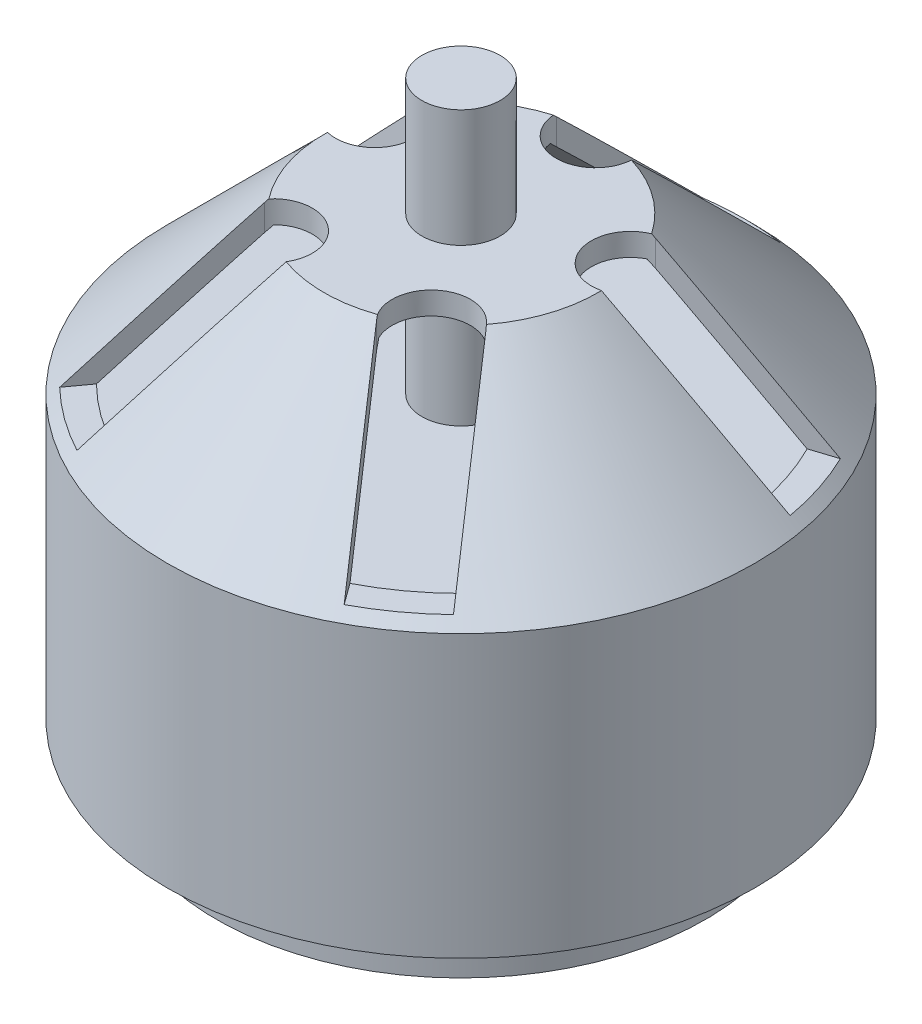
SolidWorks part; units mm, degrees
ref_plane "Front Plane" through (0, 0, 0) normal (0, 0, 1) x (1, 0, 0)
ref_plane "Top Plane" through (0, 0, 0) normal (0, 1, 0) x (1, 0, 0)
ref_plane "Right Plane" through (0, 0, 0) normal (1, 0, 0) x (0, 0, -1)
sketch "Sketch1" plane through (0, 0, 0) normal (0, 0, 1) x (1, 0, 0)
  line L0 (0, 0) -> (0, 62)
  line L1 (0, 62) -> (4, 62)
  line L2 (4, 62) -> (4, 50)
  line L3 (4, 50) -> (14.0114, 50)
  line L4 (14.0114, 50) -> (30, 34.0114)
  line L5 (30, 34.0114) -> (30, 5.2712)
  line L6 (30, 5.2712) -> (25, 5.2712)
  line L7 (25, 5.2712) -> (25, 0)
  line L8 (25, 0) -> (0, 0)
  line L9 (4, 47.694) -> (13.6548, 47.694)
  line L10 (13.6548, 47.694) -> (27.3374, 34.0114)
  line L11 (27.3374, 34.0114) -> (4, 34.0114)
  line L12 (4, 34.0114) -> (4, 47.694)
  dimension "D1" = 12
  dimension "D2" = 62
  dimension "D3" = 30
  dimension "D4" = 25
  dimension "D5" = 4
  dimension "D6" = 45
revolve "Revolve1" add sketch "Sketch1" angle 360 about L0
sketch "Sketch2" plane through (0, 50, 0) normal (0, 1, 0) x (1, 0, 0)
  line L0 (0, 0) -> (0, 17.7439) construction
  line L1 (-4, 13.7439) -> (-4, 37.2428)
  line L2 (-4, 37.2428) -> (4, 37.2428)
  line L3 (4, 37.2428) -> (4, 13.7439)
  line L4 (11.8351, 8.0513) -> (34.1839, 15.3129)
  line L5 (36.656, 7.7044) -> (14.3073, 0.4429)
  line L6 (34.1839, 15.3129) -> (36.656, 7.7044)
  line L7 (11.3145, -8.7679) -> (25.1268, -27.7789)
  line L8 (18.6547, -32.4812) -> (4.8424, -13.4702)
  line L9 (25.1268, -27.7789) -> (18.6547, -32.4812)
  line L10 (-4.8424, -13.4702) -> (-18.6547, -32.4812)
  line L11 (-25.1268, -27.7789) -> (-11.3145, -8.7679)
  line L12 (-18.6547, -32.4812) -> (-25.1268, -27.7789)
  line L13 (-14.3073, 0.4429) -> (-36.656, 7.7044)
  line L14 (-34.1839, 15.3129) -> (-11.8351, 8.0513)
  line L15 (-36.656, 7.7044) -> (-34.1839, 15.3129)
  arc A0 (-4, 13.7439) -> (4, 13.7439) centre (0, 13.7439) ccw
  arc A1 (11.8351, 8.0513) -> (14.3073, 0.4429) centre (13.0712, 4.2471) ccw
  arc A2 (11.3145, -8.7679) -> (4.8424, -13.4702) centre (8.0784, -11.119) ccw
  arc A3 (-4.8424, -13.4702) -> (-11.3145, -8.7679) centre (-8.0784, -11.119) ccw
  arc A4 (-14.3073, 0.4429) -> (-11.8351, 8.0513) centre (-13.0712, 4.2471) ccw
  point P31 (0, 0)
  dimension "D1" = 8
  dimension "D2" = 5
extrude "Cut-Extrude1" cut sketch "Sketch2" against normal blind 15
